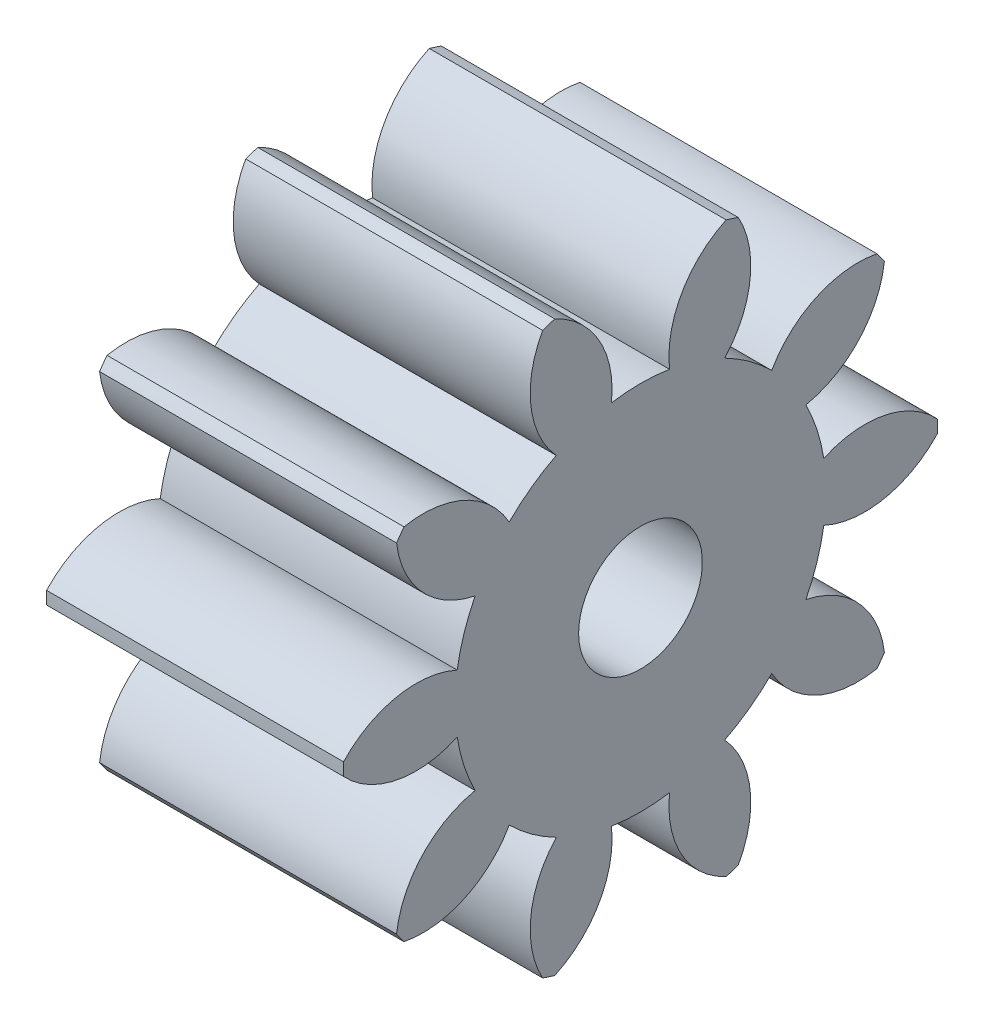
SolidWorks part; units mm, degrees
ref_plane "Plane1" through (0, 0, 0) normal (0, 0, 1) x (1, 0, 0)
ref_plane "Plane2" through (0, 0, 0) normal (0, 1, 0) x (1, 0, 0)
ref_plane "Plane3" through (0, 0, 0) normal (1, 0, 0) x (0, 0, -1)
sketch "HoldingSke" plane through (0, 0, 0) normal (0, 1, 0) x (1, 0, 0)
  line L0 (0, 0) -> (0.4924, -0.0868)
  line L1 (-15, 0) -> (100, 0) construction
  line L2 (0, 0) -> (-2.1039, 2.3779)
  line L3 (0, 0) -> (-11.863, 4.5341)
  line L4 (0, 0) -> (8.5048, 1.4996)
  line L5 (0, 0) -> (-46.8476, -17.4728)
  line L6 (0, 0) -> (-9.9476, -6.7116)
  line L7 (-2.1039, 2.3779) -> (8.6586, 51.2059)
  line L8 (-76.2, 54.61) -> (-75.3, 54.61)
  line L9 (-71.009, 38.7566) -> (-53.1078, 45.2721)
  line L10 (-76.2, 71.12) -> (104.1128, 71.12)
  line L11 (0, 0) -> (-12, 0)
  line L12 (-76.2, 101.6) -> (-76.133, 101.6)
  line L13 (24.9733, 27.94) -> (52.9518, 28.4284)
  line L14 (24.9733, 27.94) -> (24.9743, 27.94)
  line L15 (24.9733, 27.94) -> (100.4006, 29.5858)
  line L16 (-63.627, -2) -> (-12.827, -2)
  circle A0 centre (0, 0) radius 2.5
  circle A1 centre (0, 0) radius 7.499
  circle A2 centre (0, 0) radius 37.5
  circle A3 centre (0, 0) radius 2.5
  dimension "MHD" = 14.998
  dimension "Hub_dia" = 75
  dimension "Bore" = 5
  dimension "MBD" = 5
  dimension "Num_teeth" = 10
  dimension "Pitch" = 0.5
  dimension "Overall_len" = 50
  dimension "Show_teeth" = 10
  dimension "Thickness" = 12
  dimension "OAL" = 50.0001
  dimension "T_dim" = 0.9
  dimension "Ap" = 20
  dimension "H" = 19.05
  dimension "Pitch_radius" = 180.3128
  dimension "Width" = 12
  dimension "Backlash" = 0.067
  dimension "Addendum_fac" = 1
  dimension "Dedendum_fac" = 1.25
  dimension "Clearance_fac" = 0.25
  dimension "Dedendum_add" = 0.001
  dimension "Module" = 2
sketch "BasProSke" plane through (0, 0, 0) normal (0, 1, 0) x (1, 0, 0)
  line L0 (-10, 0) -> (60, 0) construction
  line L1 (0, 0) -> (0, 12)
  line L2 (0, 0) -> (12, 0)
  line L3 (12, 0) -> (12, 12)
  line L4 (12, 12) -> (0, 12)
  dimension "Thickness" = 12
  dimension "Diameter" = 24
revolve "Base-Revolve" add sketch "BasProSke" angle 360 about L0
sketch "TooCutSke" plane through (0, 0, 0) normal (1, 0, 0) x (0, 0, -1)
  line L1 (0, 0) -> (0, 107) construction
  line L2 (0, 0) -> (-1.6814, 9.8576) construction
  line L3 (0, 0) -> (-6.1153, 18.8209) construction
  line L4 (-1.6814, 9.8576) -> (-3.0576, 9.4105) construction
  arc A0 (1.1737, 7.4066) -> (-1.1737, 7.4066) centre (0, 0) ccw
  arc A1 (3.4979, 11.5054) -> (-3.4979, 11.5054) centre (0, 0) ccw
  circle A2 centre (0, 0) radius 10 construction
  circle A3 centre (0, 0) radius 9.3969 construction
  arc A4 (-1.1737, 7.4066) -> (-3.4979, 11.5054) centre (-5.1477, 7.8615) ccw
  arc A5 (3.4979, 11.5054) -> (1.1737, 7.4066) centre (5.1477, 7.8615) ccw
  dimension "Root_dia" = 14.998
  dimension "Overcut_dia" = 24.0508
  dimension "Pitch_dia" = 20
  dimension "Base_dia" = 18.7939
  dimension "Flank_rad" = 4
  dimension "Half_ang" = 18
  dimension "Half_CT" = 1.4471
extrude "ToothCut" cut sketch "TooCutSke" along normal through all
fillet "Breaks" [suppressed] radius 0.04
fillet "RootFillets" [suppressed] radius 0.501
pattern_circular "TeethCuts" count 10 every 36 about axis through (-10, 0, 0) along (1, 0, 0) of "ToothCut", "RootFillets", "Breaks"
sketch "HubNeaOneSke" plane through (0, 0, 0) normal (-1, 0, 0) x (0, 0, 1)
  circle A0 centre (0, 0) radius 7.499
  dimension "Diameter" = 14.998
extrude "HubNearOne" [suppressed] add sketch "HubNeaOneSke" along normal blind 38.0001
sketch "HubNeaBotSke" plane through (0, 0, 0) normal (-1, 0, 0) x (0, 0, 1)
  circle A0 centre (0, 0) radius 7.499
  dimension "Diameter" = 14.998
extrude "HubNearBoth" [suppressed] add sketch "HubNeaBotSke" along normal blind 19
ref_plane "FarPln" through (12, 0, 0) normal (1, 0, 0) x (0, 0, -1)
sketch "HubFarSke" plane through (12, 0, 0) normal (1, 0, 0) x (0, 0, -1)
  circle A0 centre (0, 0) radius 7.499
  dimension "Diameter" = 14.998
extrude "HubFar" [suppressed] add sketch "HubFarSke" along normal blind 19
sketch "BorSke" plane through (0, 0, 0) normal (1, 0, 0) x (0, 0, -1)
  circle A0 centre (0, 0) radius 2.5
  dimension "Diameter" = 5
extrude "Bore" cut sketch "BorSke" along normal mid plane 100.0001
sketch "KeySke" plane through (0, 0, 0) normal (1, 0, 0) x (0, 0, -1)
  line L0 (-1, 0) -> (-1, 3.4)
  line L1 (-1, 3.4) -> (1, 3.4)
  line L2 (1, 3.4) -> (1, 0)
  line L3 (0, 0) -> (0, 34) construction
  line L4 (-1, 0) -> (1, 0)
  dimension "Offset" = 3.4
  dimension "Width" = 2
extrude "Keyway" [suppressed] cut sketch "KeySke" along normal mid plane 100.0001
pattern_circular "Keyway2" [suppressed] count 2 every 90 about axis through (-10, 0, 0) along (1, 0, 0)
equation "' \"Module@HoldingSke\" = 6.35"
equation "' \"Num_teeth@HoldingSke\" = 12"
equation "' \"Ap@HoldingSke\" =  20"
equation "' \"Ap@HoldingSke\" = 20"
equation "' \"Width@HoldingSke\" = 0.5 * 25.4"
equation "' \"Hub_dia@HoldingSke\"= 1 * 25.4"
equation "' \"Hub_dia@HoldingSke\" = 1 * 25.4"
equation "' \"Overall_len@HoldingSke\" = 1.0 * 25.4"
equation "' \"Bore@HoldingSke\" = 0.75 * 25.4"
equation "' \"T_dim@HoldingSke\" = 0.1 * 25.4"
equation "' \"Width@KeySke\" = 0.25 * 25.4"
equation "' \"Show_teeth@HoldingSke\" = 13"
equation "' \"Backlash@HoldingSke\" = 0.009 * 25.4"
equation "' \"Addendum_fac@HoldingSke\" = 1.0"
equation "' \"Dedendum_fac@HoldingSke\" = 1.25"
equation "' \"Dedendum_add@HoldingSke\" = 0.00005 * 25.4"
equation "' \"Clearance_fac@HoldingSke\" = 0.25"
equation "\"Pitch@HoldingSke\" = 1 / \"Module@HoldingSke\""
equation "\"Overcut_dia@TooCutSke\" = (\"Num_teeth@HoldingSke\" + 2 * \"Addendum_fac@HoldingSke\") / \"Pitch@HoldingSke\" + 0.002 * 25.4"
equation "\"Pitch_dia@TooCutSke\" = \"Num_teeth@HoldingSke\" / \"Pitch@HoldingSke\""
equation "\"Base_dia@TooCutSke\" = \"Num_teeth@HoldingSke\" / \"Pitch@HoldingSke\" * cos((\"Ap@HoldingSke\"  * 3.14159265 / 180))"
equation "\"Root_dia@TooCutSke\" = (\"Num_teeth@HoldingSke\" + 2) / \"Pitch@HoldingSke\" - 2 * (\"Addendum_fac@HoldingSke\" + \"Dedendum_fac@HoldingSke\") / \"Pitch@HoldingSke\" - \"Dedendum_add@HoldingSke\" * 2"
equation "\"Half_ang@TooCutSke\" = 180 / \"Num_teeth@HoldingSke\""
equation "\"Half_CT@TooCutSke\" = \"Num_teeth@HoldingSke\" / \"Pitch@HoldingSke\" * sin((3.14159265 / 2 / \"Num_teeth@HoldingSke\")) / 2 - 7 * \"Backlash@HoldingSke\" / 4"
equation "\"Flank_rad@TooCutSke\" = \"Num_teeth@HoldingSke\" / \"Pitch@HoldingSke\" / 5"
equation "\"Radius@RootFillets\" = \"Clearance_fac@HoldingSke\" / \"Pitch@HoldingSke\" + \"Dedendum_add@HoldingSke\""
equation "\"Break_rad@Breaks\" = 0.02 / \"Pitch@HoldingSke\""
equation "\"Thickness@HoldingSke\" = \"Width@HoldingSke\""
equation "\"OAL@HoldingSke\" = \"Thickness@HoldingSke\""
equation "\"MHD@HoldingSke\" = (\"Num_teeth@HoldingSke\" + 2) / \"Pitch@HoldingSke\" - 2 * (\"Addendum_fac@HoldingSke\" + \"Dedendum_fac@HoldingSke\")  / \"Pitch@HoldingSke\" - \"Dedendum_add@HoldingSke\" * 2"
equation "\"MBD@HoldingSke\" = (\"Num_teeth@HoldingSke\" + 2) / \"Pitch@HoldingSke\" - 2 * (\"Addendum_fac@HoldingSke\" + \"Dedendum_fac@HoldingSke\")  / \"Pitch@HoldingSke\" - \"Dedendum_add@HoldingSke\" * 2 - 0.002 * 25.4"
equation "\"MHD@HoldingSke\" = ((sgn( \"MHD@HoldingSke\" - \"Hub_dia@HoldingSke\" )-1)*( \"MHD@HoldingSke\" - \"Hub_dia@HoldingSke\" ))/-2+ \"Hub_dia@HoldingSke\""
equation "\"MBD@HoldingSke\" = ((sgn( \"MBD@HoldingSke\" - \"Bore@HoldingSke\" )-1)*( \"MBD@HoldingSke\" - \"Bore@HoldingSke\" ))/-2+ \"Bore@HoldingSke\""
equation "\"OAL@HoldingSke\" = ((sgn( \"OAL@HoldingSke\" - \"Overall_len@HoldingSke\" )+1)*( \"OAL@HoldingSke\" - \"Overall_len@HoldingSke\" ))/2 + \"Overall_len@HoldingSke\" + 0.000002 * 25.4"
equation "\"Num_teeth@TeethCuts\" = int( \"Show_teeth@HoldingSke\" ) + 1"
equation "\"Num_teeth@TeethCuts\" = ((sgn( \"Num_teeth@TeethCuts\" - \"Num_teeth@HoldingSke\" )-1)*( \"Num_teeth@TeethCuts\" - \"Num_teeth@HoldingSke\" ))/-2+ \"Num_teeth@HoldingSke\""
equation "\"Num_teeth@TeethCuts\" = ((sgn( \"Num_teeth@TeethCuts\" - 2.0)+1)*( \"Num_teeth@TeethCuts\" - 2.0))/2 +2.0"
equation "\"Angle@TeethCuts\" = 360.0 / \"Num_teeth@HoldingSke\""
equation "\"Diameter@BasProSke\" = (\"Num_teeth@HoldingSke\" + 2 * \"Addendum_fac@HoldingSke\") / \"Pitch@HoldingSke\""
equation "\"Thickness@BasProSke\"  = \"Thickness@HoldingSke\""
equation "' \"Fillet_rad@BasProSke\" =  \"Thickness@HoldingSke\" * 0.05"
equation "' \"Fillet_rad@BasProSke\" = \"Thickness@HoldingSke\" * 0.05"
equation "\"MHD@HoldingSke\" = ((sgn( \"MHD@HoldingSke\" - \"Root_dia@TooCutSke\" )-1)*( \"MHD@HoldingSke\" - \"Root_dia@TooCutSke\" ))/-2+ \"Root_dia@TooCutSke\""
equation "\"Diameter@HubNeaOneSke\" = \"MHD@HoldingSke\""
equation "\"Length@HubNearOne\" = \"OAL@HoldingSke\" - \"Thickness@BasProSke\""
equation "\"Diameter@HubNeaBotSke\" = \"MHD@HoldingSke\""
equation "\"Length@HubNearBoth\" = ( \"OAL@HoldingSke\" - \"Thickness@BasProSke\" ) / 2.0"
equation "\"Thickness@FarPln\" = \"Thickness@BasProSke\""
equation "\"Diameter@HubFarSke\" = \"MHD@HoldingSke\""
equation "\"Length@HubFar\" = ( \"OAL@HoldingSke\" - \"Thickness@BasProSke\" ) / 2.0"
equation "\"Diameter@BorSke\" = \"MBD@HoldingSke\""
equation "\"D1@Bore\" = \"OAL@HoldingSke\" * 2.0"
equation "\"D1@Keyway\" = \"OAL@HoldingSke\" * 2.0"
equation "\"Offset@KeySke\" = \"T_dim@HoldingSke\" + \"MBD@HoldingSke\" / 2.0"
